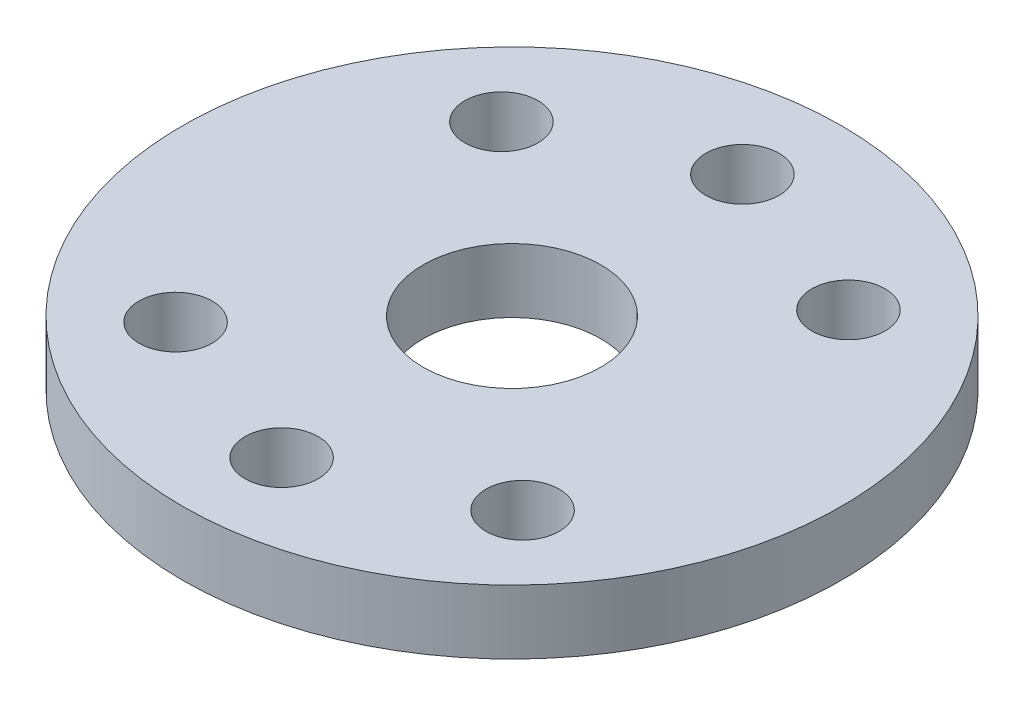
SolidWorks part; units mm, degrees
ref_plane "Спереди" through (0, 0, 0) normal (0, 0, 1) x (1, 0, 0)
ref_plane "Сверху" through (0, 0, 0) normal (0, 1, 0) x (1, 0, 0)
ref_plane "Справа" through (0, 0, 0) normal (1, 0, 0) x (0, 0, -1)
sketch "Эскиз1" plane through (0, 0, 0) normal (0, 1, 0) x (1, 0, 0)
  circle A0 centre (0, 0) radius 4.85
  circle A1 centre (0, 0) radius 18
extrude "Вытянуть1" add sketch "Эскиз1" along normal blind 3.5
sketch "Эскиз2" plane through (0, 3.5, 0) normal (0, 1, 0) x (1, 0, 0)
  circle A0 centre (-0.409, 12.9936) radius 2
  circle A1 centre (-9.477, 8.8986) radius 2
  circle A2 centre (8.8986, 9.477) radius 2
  circle A3 centre (9.477, -8.8986) radius 2
  circle A4 centre (0.409, -12.9936) radius 2
  circle A5 centre (-8.8986, -9.477) radius 2
extrude "Вырез-Вытянуть1" cut sketch "Эскиз2" against normal through all
